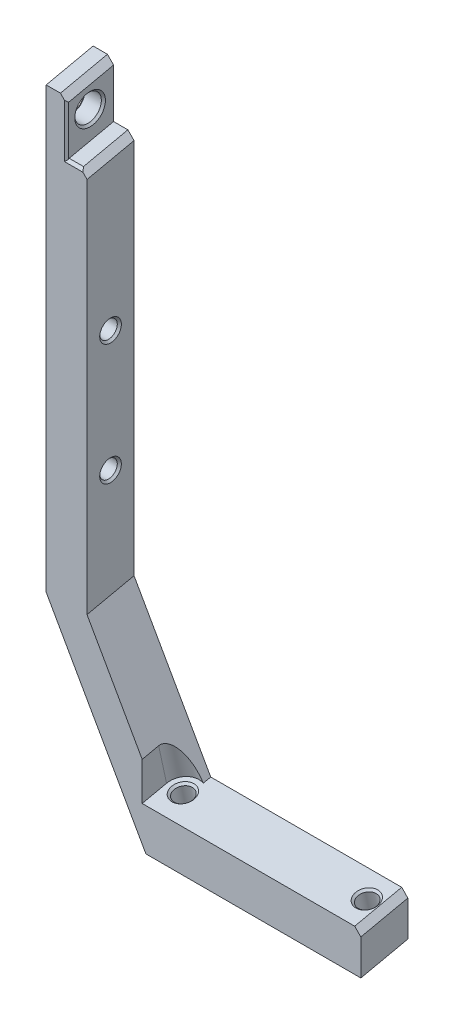
SolidWorks part; units mm, degrees
ref_plane "Top" through (0, 0, 0) normal (0, 0, 1) x (1, 0, 0)
ref_plane "Front" through (0, 0, 0) normal (0, 1, 0) x (1, 0, 0)
ref_plane "Right" through (0, 0, 0) normal (1, 0, 0) x (0, 0, -1)
sketch "Sketch4" plane through (0, 0, 0) normal (1, 0, 0) x (0, 0, -1)
  line L1 (0, 0) -> (11.5, 0)
  line L2 (0, 0) -> (0, 144)
  line L3 (0, 144) -> (11.5, 144)
  line L4 (11.5, 0) -> (11.5, 144)
  dimension "D1" = 11.5
  dimension "D2" = 144
extrude "Boss-Extrude2" add sketch "Sketch4" along normal blind 10
sketch "Sketch6" plane through (10, 0, 0) normal (1, 0, 0) x (0, 0, -1)
  line L0 (5.75, 0) -> (11.5, 1.2463)
  line L1 (0, 0) -> (11.5, 0) construction
  line L2 (11.5, 0) -> (11.5, 144) construction
  line L3 (11.5, 1.2463) -> (9.3816, 11.0194)
  line L4 (9.3816, 11.0194) -> (-0.3914, 8.901)
  line L5 (-0.3914, 8.901) -> (1.7269, -0.872)
  line L6 (1.7269, -0.872) -> (5.75, 0)
  line L7 (0, 144) -> (0, 0) construction
  dimension "D1" = 10
  dimension "D2" = 10
  dimension "D3" = 77.77
  dimension "D4" = 12.23
extrude "Boss-Extrude3" add sketch "Sketch6" along normal blind 67 and the other way blind 10
ref_plane "Plane2" through (0, 0.3184, -1.4689) normal (0, -0.2118, 0.9773) x (1, 0, 0)
ref_plane "Plane3" through (0, 137.538, 29.8122) normal (0, 0.9773, 0.2118) x (1, 0, 0)
sketch "Sketch26" plane through (0, 2.4368, -11.242) normal (0, 0.2118, -0.9773) x (-1, 0, 0)
  line L0 (-23, -1.2181) -> (0, 38.6191)
  line L1 (-10, -1.2181) -> (-77, -1.2181) construction
  line L2 (0, -2.4361) -> (0, 138.2958) construction
  line L3 (0, 38.6191) -> (-8.6603, 43.6191)
  line L5 (-8.6603, 43.6191) -> (-31.6603, 3.7819)
  line L7 (-23, -1.2181) -> (-31.6603, 3.7819)
  dimension "D1" = 23
  dimension "D2" = 60
  dimension "D3" = 10
extrude "Boss-Extrude6" add sketch "Sketch26" along normal up to surface and the other way up to surface up to face at (6, 57.8493, -11.5) other way up to face at (5, 3.5476, 0)
sketch "Sketch7" plane through (10, 0, 0) normal (1, 0, 0) x (0, 0, -1)
  line L0 (-2.9728, -1.8907) -> (11.8209, -3.029)
  line L2 (11.8209, -3.029) -> (11.8209, 1.3159)
  line L3 (11.8209, 1.3159) -> (-2.9728, -1.8907)
  line L4 (1.7269, -0.872) -> (11.5, 1.2463) construction
extrude "Cut-Extrude2" cut sketch "Sketch7" against normal blind 10
sketch "Sketch8" plane through (0, 8.5826, 1.8603) normal (0, 0.9773, 0.2118) x (1, 0, 0)
  line L1 (77, 11.503) -> (77, 1.503) construction
  line L2 (28.7735, 11.503) -> (77, 11.503) construction
  circle A0 centre (72.5, 8.003) radius 2.25
  circle A1 centre (27.5, 8.003) radius 2.25
  dimension "D2" = 4.5
  dimension "D3" = 4.5
  dimension "D1" = 45
  dimension "D4" = 3.5
  dimension "D5" = 4.5
extrude "Cut-Extrude3" cut sketch "Sketch8" against normal through all
sketch "Sketch11" plane through (0, 8.5826, 1.8603) normal (0, 0.9773, 0.2118) x (1, 0, 0)
  line L0 (23.5, 8.003) -> (23.5, 0)
  line L1 (23.5, 0) -> (31.5, 0)
  line L3 (31.5, 0) -> (31.5, 8.003)
  line L4 (10, 0) -> (0, 0) construction
  circle A0 centre (27.5, 8.003) radius 4 construction
  arc A1 (31.5, 8.003) -> (23.5, 8.003) centre (27.5, 8.003) ccw
  dimension "D1" = 8
sketch "Sketch12" plane through (77, 0, 0) normal (1, 0, 0) x (0, 0, -1)
  line L7 (1.7269, -0.872) -> (0, -1.2463)
  line L8 (0, -1.2463) -> (0, 7.0952)
  line L10 (0, 7.0952) -> (1.7269, -0.872)
extrude "Boss-Extrude4" add sketch "Sketch12" against normal up to surface (77 mm away) up to face at (0, 34.8174, -2.8748)
sketch "Sketch13" plane through (10, 0, 0) normal (1, 0, 0) x (0, 0, -1)
  line L0 (11.5, 144) -> (11.5, 152)
  line L1 (11.5, 152) -> (0, 149.5073)
  line L2 (0, 149.5073) -> (0, 144)
  line L3 (0, 144) -> (11.5, 144)
  line L4 (9.3816, 11.0194) -> (-0.3914, 8.901) construction
  dimension "D1" = 8
extrude "Boss-Extrude5" add sketch "Sketch13" against normal blind 10
sketch "Sketch14" plane through (10, 0, 0) normal (1, 0, 0) x (0, 0, -1)
  line L0 (11.5, 44.7503) -> (11.5, 152) construction
  circle A0 centre (5.75, 144) radius 3.25
  dimension "D2" = 6.5
  dimension "D1" = 8
  dimension "D3" = 5.75
extrude "Cut-Extrude5" cut sketch "Sketch14" against normal blind 10
sketch "Sketch29" plane through (77, 0, 0) normal (1, 0, 0) x (0, 0, -1)
  line L0 (0, 7.0952) -> (0, 8.9859)
  line L1 (0, 8.9859) -> (-0.3914, 8.901)
  line L2 (-0.3914, 8.901) -> (0, 7.0952)
extrude "Cut-Extrude10" cut sketch "Sketch29" against normal through all
sketch "Sketch18" plane through (10, 0, 0) normal (1, 0, 0) x (0, 0, -1)
  line L0 (5.75, 99.6) -> (5.75, 70)
  line L1 (11.5, 44.7503) -> (11.5, 152) construction
  dimension "D1" = 5.75
  dimension "D2" = 29.6
  dimension "D3" = 70
sketch "Sketch31" plane through (77, 0, 0) normal (1, 0, 0) x (0, 0, -1)
  line L0 (11.5, 1.2463) -> (9.3816, 11.0194)
  line L1 (9.3816, 11.0194) -> (11.5, 11.4786)
  line L2 (11.5, 6.3625) -> (11.5, 44.7503) construction
  line L3 (11.5, 11.4786) -> (11.5, 1.2463)
extrude "Boss-Extrude7" add sketch "Sketch31" against normal up to surface (77 mm away) up to face at (0, 75.3768, -5.75)
hole_wizard "M4 Clearance Hole1" positions "Sketch19" profile "Sketch20" hole size "M4" standard "DIN" end condition through all
sketch "Sketch19" plane through (10, 0, 0) normal (1, 0, 0) x (0, 0, -1)
  point P0 (5.75, 70)
  point P3 (5.75, 99.6)
sketch "Sketch20" plane through (10, 70, -5.75) normal (0, 1, 0) x (0, 0, -1)
  line L0 (0, 0) -> (0, 10)
  line L1 (0, 10) -> (2.15, 10)
  line L2 (2.15, 10) -> (2.15, 0)
  line L5 (2.15, 0) -> (0, 0)
  line L11 (0, -6.35) -> (0, 107.95) construction
  dimension "Thru Hole Dia." = 4.3
  dimension "Thru Hole Depth" = 10
sketch "Sketch24" plane through (10, 0, 0) normal (1, 0, 0) x (0, 0, -1)
  line L0 (11.5, 152) -> (0, 149.5073)
  line L1 (0, 149.5073) -> (0, 136)
  line L2 (0, 149.5073) -> (0, 42.2576) construction
  line L3 (0, 136) -> (11.5, 138.4927)
  line L4 (11.5, 11.4786) -> (11.5, 24.2859) construction
  line L5 (11.5, 138.4927) -> (11.5, 152)
  circle A0 centre (5.75, 144) radius 3.25 construction
  dimension "D1" = 8
extrude "Cut-Extrude7" cut sketch "Sketch24" against normal blind 5
chamfer "Chamfer2" distance 0.5 angle 45 8 edges at (10, 70, -7.9) (0, 70, -7.9) (10, 99.6, -7.9) (0, 99.6, -7.9) (0, 144, -9) (5, 144, -9) (72.5, 9.8013, -3.7621) (72.5, 0.9816, -10.2784)
chamfer "Chamfer5" distance 0.5 angle 45 2 edges at (7.5, 136, 0) (5, 142.7537, 0)
chamfer "Chamfer6" distance 1.5 angle 45 2 edges at (5, 150.8078, -6) (10, 137.3155, -6.0692)
chamfer "Chamfer7" distance 1.5 angle 45 1 edges at (77, 10.2322, -5.75)
sketch "Sketch28" plane through (0, 0.0079, -11.5) normal (0, 0, 1) x (-1, 0, 0)
  line L0 (-215.5088, 339.9396) -> (8.299, 9.2449)
  line L1 (8.299, 9.2449) -> (8.299, -56.7089)
  line L2 (8.299, -56.7089) -> (-215.5088, 339.9396)
  line L3 (-10, -24.278) -> (-17.2265, -11.4707) construction
extrude "Cut-Extrude8" cut sketch "Sketch28" against normal through all and the other way through all
ref_plane "Plane1" through (87, 0, 0) normal (1, 0, 0) x (0, 0, -1)
extrude "Cut-Extrude9" cut sketch "Sketch11" along normal through all
chamfer "Chamfer10" distance 0.5 angle 45 2 edges at (27.5, 9.8013, -3.7621) (27.5, 0.9816, -10.2784)
